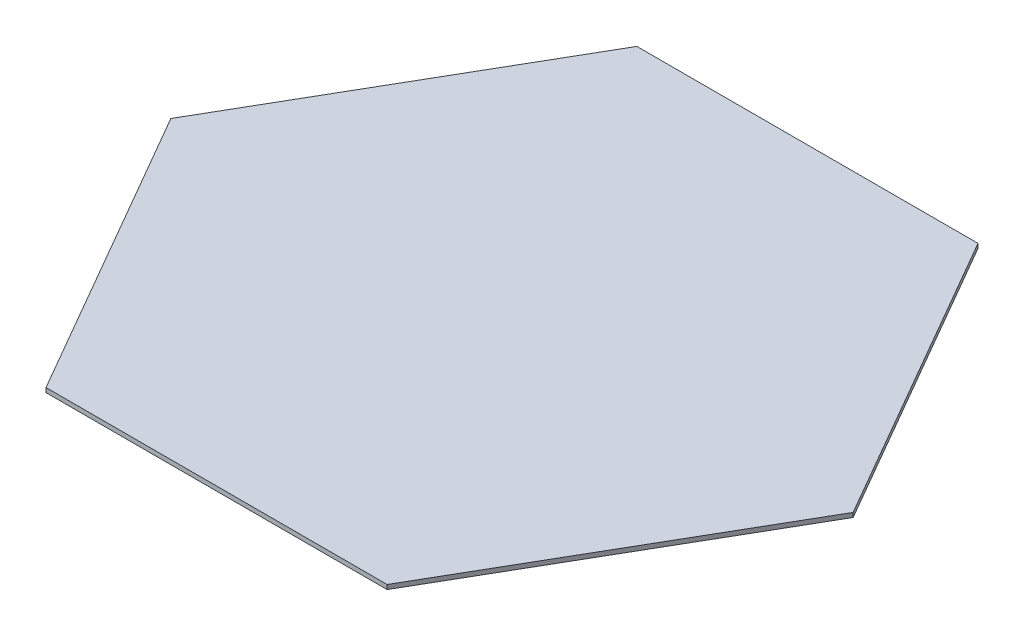
SolidWorks part; units mm, degrees
ref_plane "Front Plane" through (0, 0, 0) normal (0, 0, 1) x (1, 0, 0)
ref_plane "Top Plane" through (0, 0, 0) normal (0, 1, 0) x (1, 0, 0)
ref_plane "Right Plane" through (0, 0, 0) normal (1, 0, 0) x (0, 0, -1)
sketch "Sketch2" plane through (0, 0, 0) normal (0, 1, 0) x (1, 0, 0)
  line L1 (230.9401, 0) -> (115.4701, 200)
  line L2 (115.4701, 200) -> (-115.4701, 200)
  line L3 (-115.4701, 200) -> (-230.9401, 0)
  line L4 (-230.9401, 0) -> (-115.4701, -200)
  line L5 (-115.4701, -200) -> (115.4701, -200)
  line L6 (115.4701, -200) -> (230.9401, 0)
  circle A0 centre (0, 0) radius 200 construction
extrude "Boss-Extrude1" add sketch "Sketch2" along normal blind 3
sketch "Sketch3" plane through (0, 3, 0) normal (0, 1, 0) x (1, 0, 0)
  line L4 (4.7052, -104.5427) -> (32.2052, -104.5427)
  line L5 (-115.4701, -200) -> (115.4701, -200) construction
  line L6 (-115.4701, -200) -> (-230.9401, 0)
  line L8 (230.9401, 0) -> (115.4701, -200)
  line L10 (-230.9401, 0) -> (-115.4701, 200)
  line L11 (-115.4701, 200) -> (115.4701, 200)
  line L12 (1.7052, -149.6867) -> (-38.5448, -149.6867)
  line L16 (79.7052, -170.8876) -> (52.2052, -170.8876)
  line L17 (115.4701, 200) -> (230.9401, 0)
  line L18 (-38.2948, -190) -> (1.7052, -190)
  line L19 (1.7052, -147.5867) -> (-38.5448, -147.5867)
  line L20 (-38.2948, -187.95) -> (1.7052, -187.95)
  line L21 (1.7052, -147.5867) -> (1.7052, -149.6867)
  line L22 (-38.5448, -147.5867) -> (-38.5448, -149.6867)
  line L23 (-38.2948, -190) -> (-38.2948, -187.95)
  line L24 (1.7052, -190) -> (1.7052, -187.95)
  line L25 (79.7052, -167.8876) -> (52.2052, -167.8876)
  line L27 (7.8052, -107.5427) -> (32.2052, -107.5427)
  line L28 (79.7052, -170.8876) -> (79.7052, -167.8876)
  line L29 (79.7052, -104.5427) -> (79.7052, -107.5427)
  line L32 (248.1976, -104.5427) -> (79.7052, -104.5427) construction
  line L35 (79.7052, -170.8876) -> (248.1976, -170.8876) construction
  line L36 (248.1976, -104.5427) -> (248.1976, -170.8876) construction
  line L38 (79.7052, -167.8876) -> (245.1976, -167.8876) construction
  line L39 (245.1976, -107.5427) -> (79.7052, -107.5427) construction
  line L40 (245.1976, -107.5427) -> (245.1976, -167.8876) construction
  line L42 (4.7052, -104.5427) -> (4.7052, -170.8876)
  line L44 (-115.4701, -200) -> (115.4701, -200)
  line L45 (7.8052, -167.8876) -> (7.8052, -107.5427)
  line L46 (1.7052, -190) -> (-121.2436, -190) construction
  line L47 (32.2052, -170.8876) -> (32.2052, -167.8876)
  line L49 (52.2052, -167.8876) -> (52.2052, -170.8876)
  line L50 (32.2052, -167.8876) -> (7.8052, -167.8876)
  line L51 (32.2052, -170.8876) -> (4.7052, -170.8876)
  line L52 (32.2052, -104.5427) -> (32.2052, -107.5427)
  line L53 (52.2052, -104.5427) -> (52.2052, -107.5427)
  line L54 (52.2052, -107.5427) -> (79.7052, -107.5427)
  line L55 (52.2052, -104.5427) -> (79.7052, -104.5427)
  point P1 (115.4701, 200)
  point P23 (-99.195, 0)
  dimension "D1" = 82.9488
  dimension "D7" = 3.1
  dimension "D8" = 10
  dimension "D5" = 2.05
  dimension "D9" = 2.1
  dimension "D6" = 3
